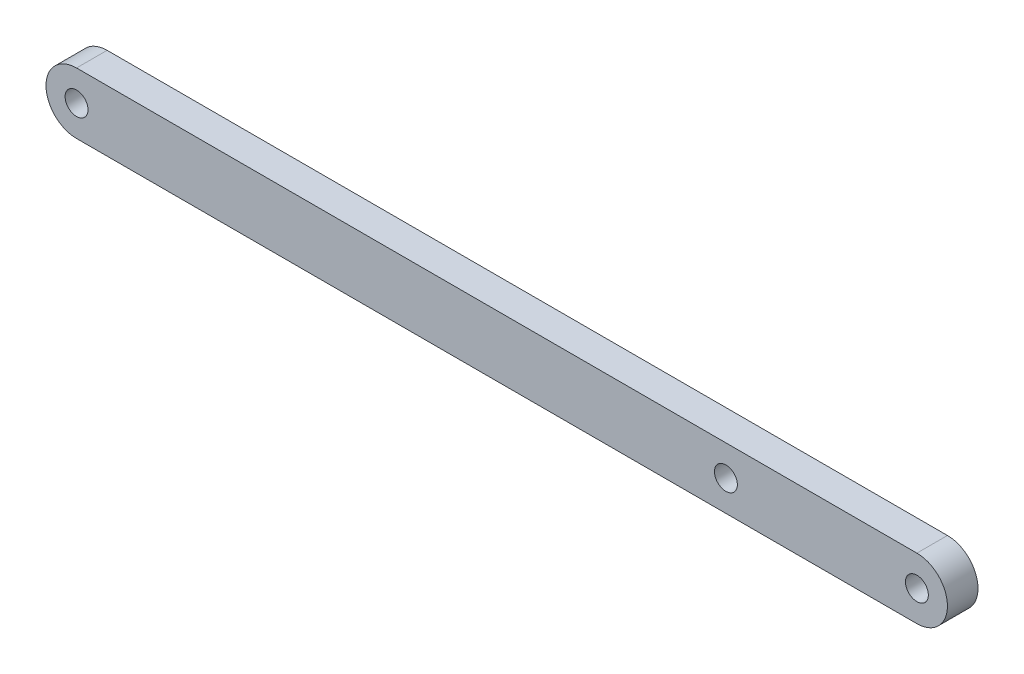
SolidWorks part; units mm, degrees
ref_plane "Front Plane" through (0, 0, 0) normal (0, 0, 1) x (1, 0, 0)
ref_plane "Top Plane" through (0, 0, 0) normal (0, 1, 0) x (1, 0, 0)
ref_plane "Right Plane" through (0, 0, 0) normal (1, 0, 0) x (0, 0, -1)
sketch "Sketch1" plane through (0, 0, 0) normal (0, 0, 1) x (1, 0, 0)
  line L0 (55, 0) -> (-55, 0) construction
  line L1 (55, -4) -> (-55, -4)
  line L2 (55, 4) -> (-55, 4)
  arc A0 (55, -4) -> (55, 4) centre (55, 0) ccw
  arc A1 (-55, 4) -> (-55, -4) centre (-55, 0) ccw
  circle A2 centre (-55, 0) radius 1.5
  circle A3 centre (55, 0) radius 1.5
  point P3 (0, 0)
  dimension "D3" = 3
  dimension "4" = 4
  dimension "D4" = 3
  dimension "D1" = 110
  dimension "D2" = 55
extrude "Boss-Extrude1" add sketch "Sketch1" along normal blind 4
sketch "Sketch2" plane through (0, 0, 4) normal (0, 0, 1) x (1, 0, 0)
  line L0 (-55, -4) -> (55, -4) construction
  circle A0 centre (30, 0) radius 1.5
  circle A1 centre (55, 0) radius 1.5 construction
  dimension "D1" = 3
  dimension "D2" = 25
  dimension "D3" = 4
extrude "Cut-Extrude1" cut sketch "Sketch2" against normal blind 10
